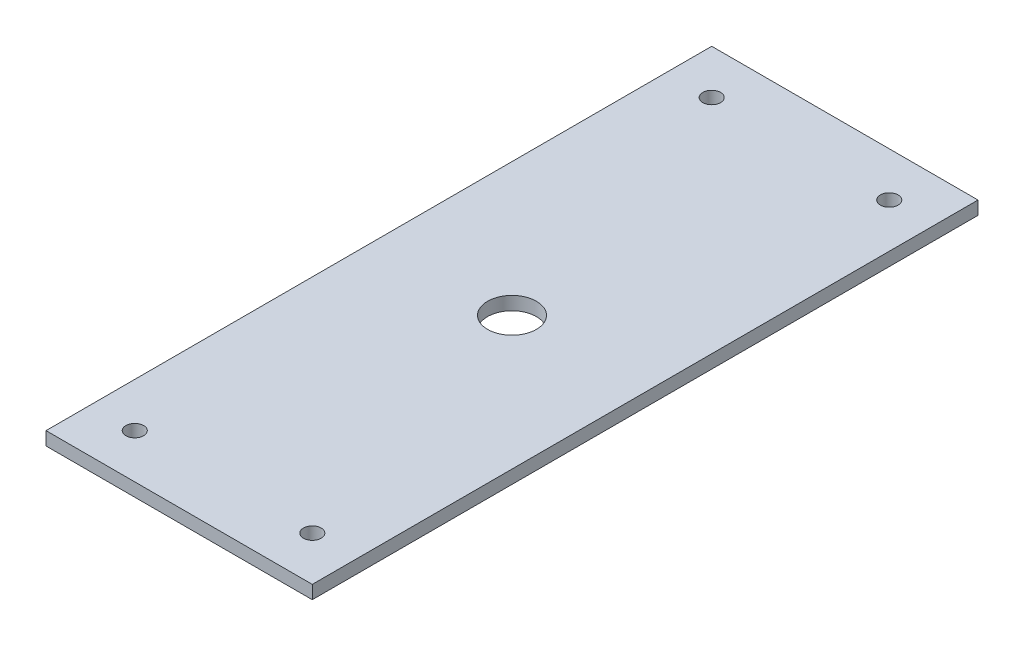
SolidWorks part; units mm, degrees
ref_plane "Front Plane" through (0, 0, 0) normal (0, 0, 1) x (1, 0, 0)
ref_plane "Top Plane" through (0, 0, 0) normal (0, 1, 0) x (1, 0, 0)
ref_plane "Right Plane" through (0, 0, 0) normal (1, 0, 0) x (0, 0, -1)
sketch "Sketch1" plane through (0, 0, 0) normal (0, 1, 0) x (1, 0, 0)
  line L1 (60, 150) -> (-60, 150)
  line L2 (60, 150) -> (60, -150)
  line L3 (60, -150) -> (-60, -150)
  line L4 (-60, 150) -> (-60, -150)
  line L5 (40, 100) -> (-40, -100) construction
  line L7 (40, 150) -> (40, -150) construction
  line L8 (60, -170) -> (-60, -170)
  line L9 (40, 130) -> (-40, 130) construction
  line L11 (40, 130) -> (40, -130) construction
  line L12 (-40, 130) -> (-40, -130) construction
  line L13 (60, 130) -> (-60, 130) construction
  line L14 (-40, 150) -> (-40, -150) construction
  line L17 (40, -130) -> (-40, -130) construction
  line L18 (40, -100) -> (-40, 100) construction
  circle A0 centre (-40, 130) radius 4
  circle A1 centre (40, 130) radius 4
  circle A2 centre (-40, -130) radius 4
  circle A3 centre (40, -130) radius 4
  circle A4 centre (0, 0) radius 11
  point P0 (0, 0)
  dimension "D3" = 22
  dimension "D1" = 120
  dimension "D2" = 300
  dimension "D4" = 20
  dimension "D5" = 20
  dimension "D6" = 20
extrude "Boss-Extrude1" add sketch "Sketch1" along normal blind 6 contours L1 L4 L3 L2 A4 A3 A2 A1 A0
